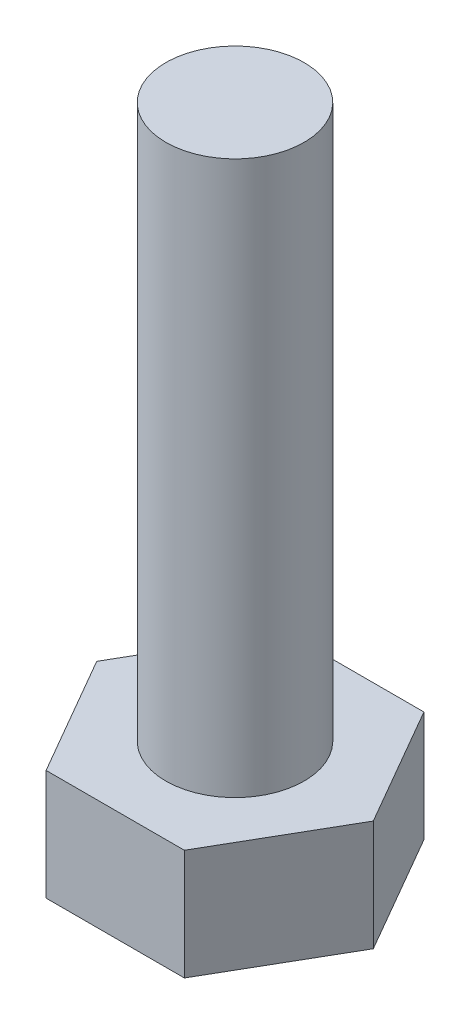
SolidWorks part; units mm, degrees
material "0.6020 (EN-GJL-200)"
ref_plane "前视基准面" through (0, 0, 0) normal (0, 0, 1) x (1, 0, 0)
ref_plane "上视基准面" through (0, 0, 0) normal (0, 1, 0) x (1, 0, 0)
ref_plane "右视基准面" through (0, 0, 0) normal (1, 0, 0) x (0, 0, -1)
other "Configuration Table"
sketch "草图1" plane through (0, 0, 0) normal (0, 1, 0) x (1, 0, 0)
  line L1 (1.25, 2.1651) -> (-1.25, 2.1651)
  line L2 (-1.25, 2.1651) -> (-2.5, 0)
  line L3 (-2.5, 0) -> (-1.25, -2.1651)
  line L4 (-1.25, -2.1651) -> (1.25, -2.1651)
  line L5 (1.25, -2.1651) -> (2.5, 0)
  line L6 (2.5, 0) -> (1.25, 2.1651)
  circle A0 centre (0, 0) radius 2.1651 construction
  dimension "D1" = 2.5
extrude "凸台-拉伸1" add sketch "草图1" along normal blind 2
sketch "草图2" plane through (0, 2, 0) normal (0, 1, 0) x (1, 0, 0)
  circle A0 centre (0, 0) radius 1.25
  dimension "D1" = 2.5
extrude "凸台-拉伸2" add sketch "草图2" along normal blind 10
